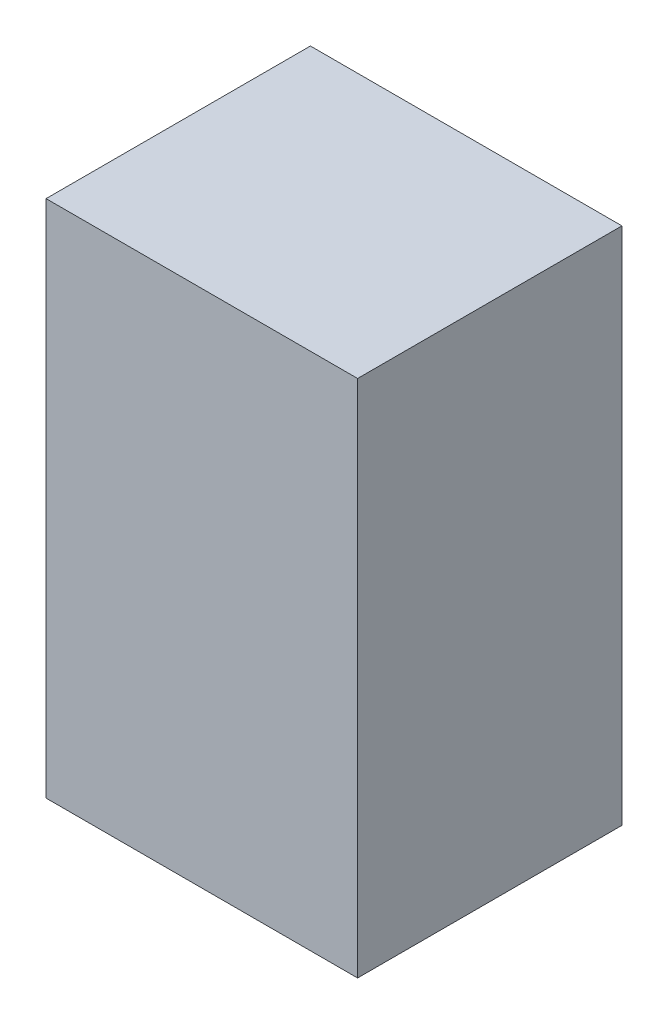
SolidWorks part; units mm, degrees
ref_plane "Front Plane" through (0, 0, 0) normal (0, 0, 1) x (1, 0, 0)
ref_plane "Top Plane" through (0, 0, 0) normal (0, 1, 0) x (1, 0, 0)
ref_plane "Right Plane" through (0, 0, 0) normal (1, 0, 0) x (0, 0, -1)
sketch "Sketch1" plane through (0, 0, 0) normal (0, 1, 0) x (1, 0, 0)
  line L1 (-419.1, -355.6) -> (419.1, -355.6)
  line L2 (-419.1, -355.6) -> (-419.1, 355.6)
  line L3 (-419.1, 355.6) -> (419.1, 355.6)
  line L4 (419.1, -355.6) -> (419.1, 355.6)
  line L5 (-419.1, -355.6) -> (419.1, 355.6) construction
  line L6 (-419.1, 355.6) -> (419.1, -355.6) construction
  point P0 (0, 0)
extrude "Boss-Extrude1" add sketch "Sketch1" along normal blind 1397
